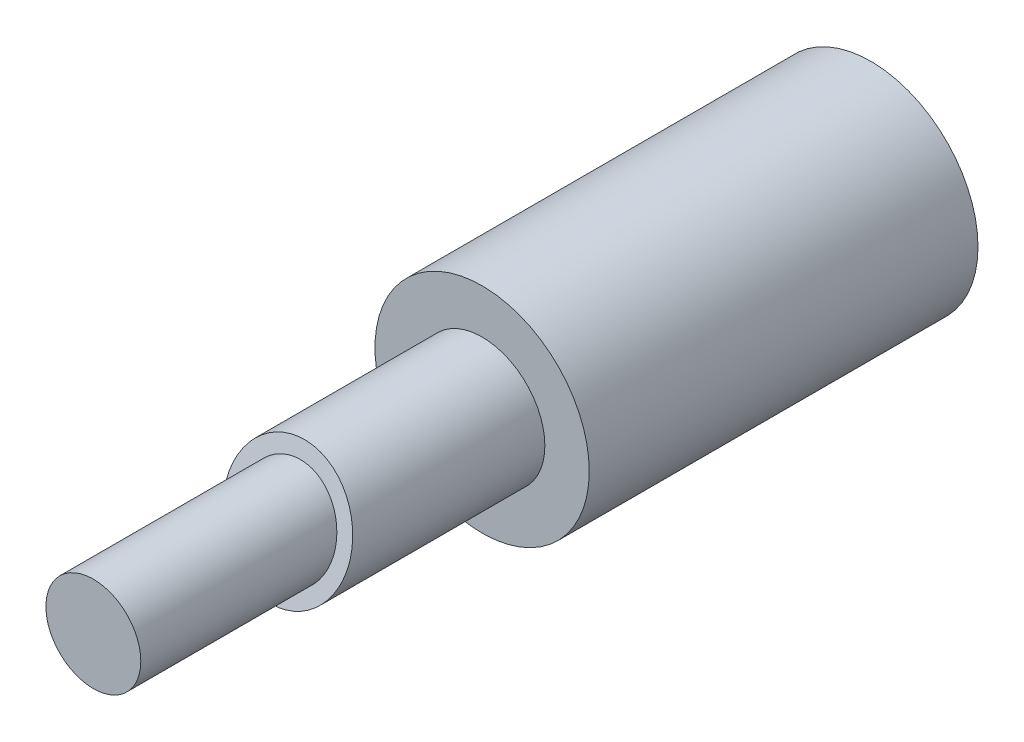
SolidWorks part; units mm, degrees
ref_plane "Front Plane" through (0, 0, 0) normal (0, 0, 1) x (1, 0, 0)
ref_plane "Top Plane" through (0, 0, 0) normal (0, 1, 0) x (1, 0, 0)
ref_plane "Right Plane" through (0, 0, 0) normal (1, 0, 0) x (0, 0, -1)
sketch "Sketch4" plane through (0, 0, 0) normal (0, 1, 0) x (1, 0, 0)
  line L0 (0, 0) -> (0, 101.6) construction
  line L1 (0, 101.6) -> (14, 101.6)
  line L2 (14, 101.6) -> (14, 50.8)
  line L3 (14, 50.8) -> (8.2, 50.8)
  line L4 (8.2, 50.8) -> (8.2, 25.4)
  line L5 (8.2, 25.4) -> (6.2, 25.4)
  line L6 (6.2, 25.4) -> (6.2, 0)
  line L7 (6.2, 0) -> (0, 0)
  line L8 (0, 0) -> (0, 101.6)
  dimension "D1" = 25.4
  dimension "D2" = 25.4
  dimension "D3" = 50.8
  dimension "D4" = 14
  dimension "D5" = 6.2
  dimension "D6" = 2
revolve "Revolve1" add sketch "Sketch4" angle 360 about L0
draft "Draft1" type of draft neutral plane draft angle 15 neutral plane "Top Plane" faces to draft 1 face at (8.2, 0, -25.4) neutral plane through (0, 0, 0) neutral plane normal (0, 1, 0) parameters "D1"=15
